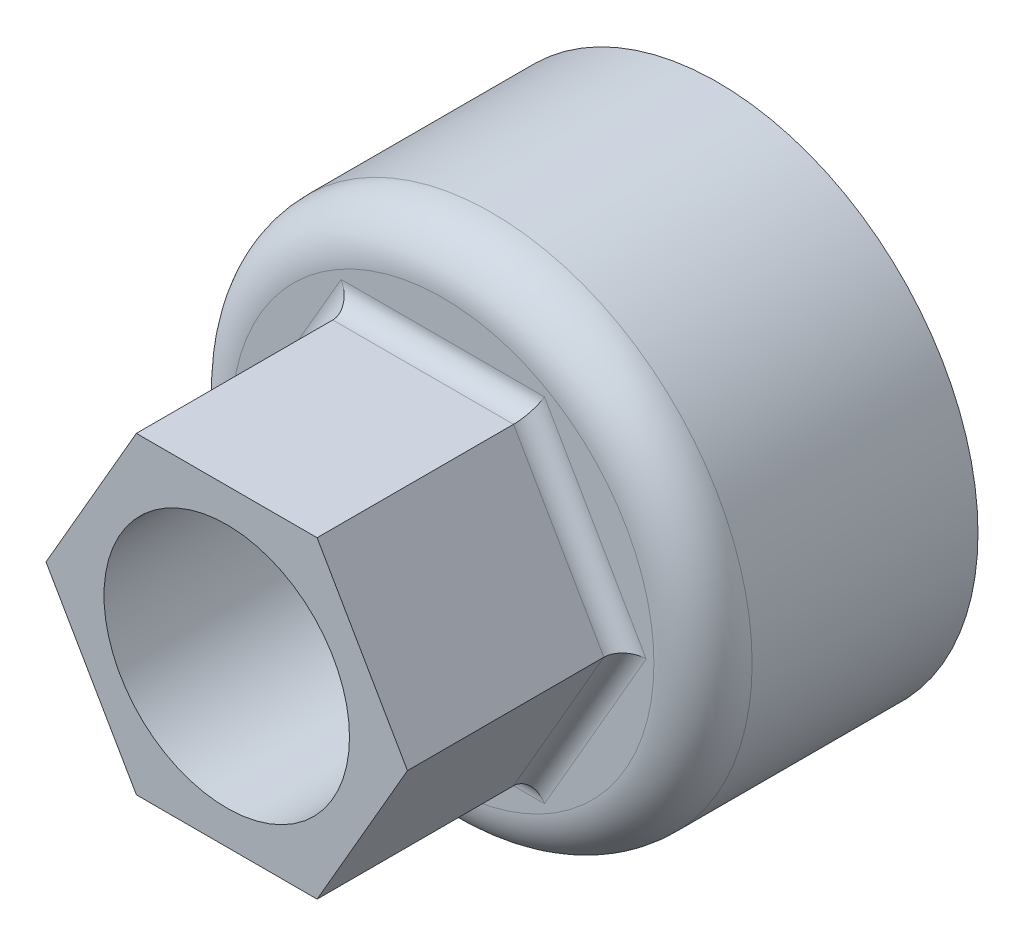
SolidWorks part; units mm, degrees
ref_plane "Top Plane" through (0, 0, 0) normal (0, 0, 1) x (1, 0, 0)
ref_plane "Front Plane" through (0, 0, 0) normal (0, 1, 0) x (1, 0, 0)
ref_plane "Right Plane" through (0, 0, 0) normal (1, 0, 0) x (0, 0, -1)
sketch "Sketch1" plane through (0, 0, 0) normal (0, 0, 1) x (1, 0, 0)
  line L1 (10.4212, 18.05) -> (-10.4212, 18.05)
  line L2 (-10.4212, 18.05) -> (-20.8423, 0)
  line L3 (-20.8423, 0) -> (-10.4212, -18.05)
  line L4 (-10.4212, -18.05) -> (10.4212, -18.05)
  line L5 (10.4212, -18.05) -> (20.8423, 0)
  line L6 (20.8423, 0) -> (10.4212, 18.05)
  circle A0 centre (0, 0) radius 18.05 construction
  circle A1 centre (0, 0) radius 26.5
  dimension "D2" = 53
  dimension "D1" = 36.1
extrude "Boss-Extrude1" add sketch "Sketch1" along normal blind 25
sketch "Sketch2" plane through (0, 0, 25) normal (0, 0, 1) x (1, 0, 0)
  circle A0 centre (0, 0) radius 26.5 construction
  circle A1 centre (0, 0) radius 26.5
extrude "Boss-Extrude2" add sketch "Sketch2" along normal blind 25
sketch "Sketch3" plane through (0, 0, 50) normal (0, 0, 1) x (1, 0, 0)
  line L1 (9.2018, 15.938) -> (-9.2018, 15.938)
  line L2 (-9.2018, 15.938) -> (-18.4036, 0)
  line L3 (-18.4036, 0) -> (-9.2018, -15.938)
  line L4 (-9.2018, -15.938) -> (9.2018, -15.938)
  line L5 (9.2018, -15.938) -> (18.4036, 0)
  line L6 (18.4036, 0) -> (9.2018, 15.938)
  circle A0 centre (0, 0) radius 26.5 construction
  circle A1 centre (0, 0) radius 26.5
  circle A2 centre (0, 0) radius 15.938 construction
extrude "Cut-Extrude1" cut sketch "Sketch3" against normal blind 22
fillet "Fillet1" radius 2 6 edges at (13.8027, 7.969, 28) (0, 15.938, 28) (-13.8027, 7.969, 28) (-13.8027, -7.969, 28) (0, -15.938, 28) (13.8027, -7.969, 28)
fillet "Fillet2" radius 5 6 edges at (0, 18.05, 25) (-15.6318, 9.025, 25) (-15.6318, -9.025, 25) (0, -18.05, 25) (15.6318, -9.025, 25) (15.6318, 9.025, 25)
fillet "Fillet3" radius 5 1 edges at (26.5, 0, 28)
sketch "Sketch4" plane through (0, 0, 50) normal (0, 0, 1) x (1, 0, 0)
  circle A0 centre (0, 0) radius 12.5
  dimension "D1" = 25
extrude "Cut-Extrude2" cut sketch "Sketch4" against normal through all
